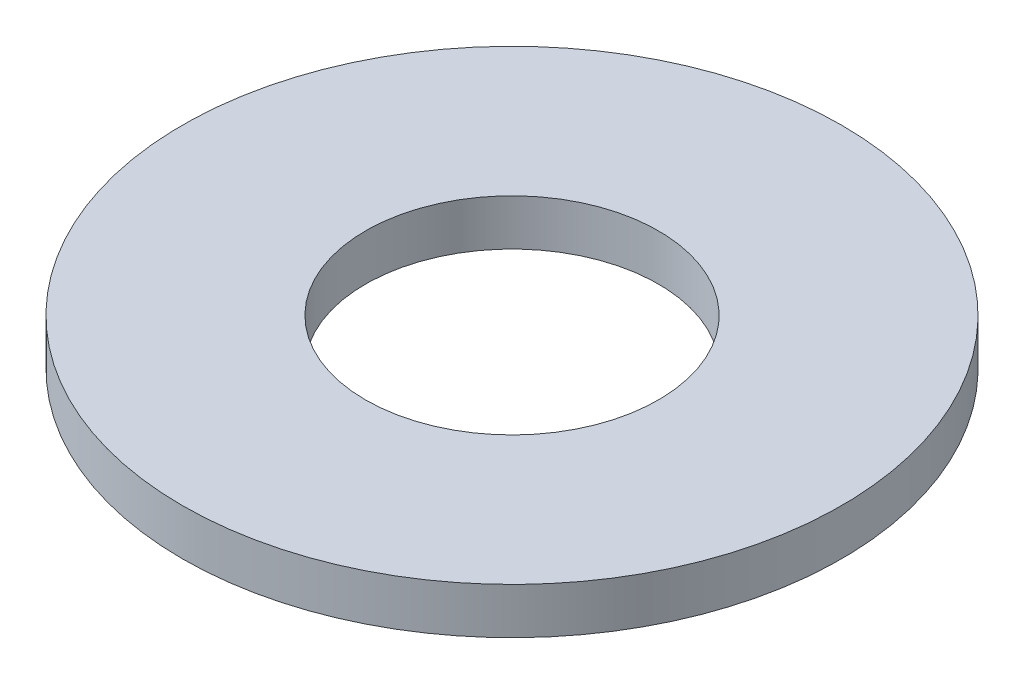
SolidWorks part; units mm, degrees
material "Plain Carbon Steel"
ref_plane "Front Plane" through (0, 0, 0) normal (0, 0, 1) x (1, 0, 0)
ref_plane "Top Plane" through (0, 0, 0) normal (0, 1, 0) x (1, 0, 0)
ref_plane "Right Plane" through (0, 0, 0) normal (1, 0, 0) x (0, 0, -1)
sketch "Sketch1" plane through (0, 0, 0) normal (0, 1, 0) x (1, 0, 0)
  circle A0 centre (0, 0) radius 3.175
  circle A1 centre (0, 0) radius 7.1438
  dimension "Washer_ID" = 6.35
  dimension "Washer_OD" = 14.2875
extrude "Washer_Body" add sketch "Sketch1" along normal blind 1
